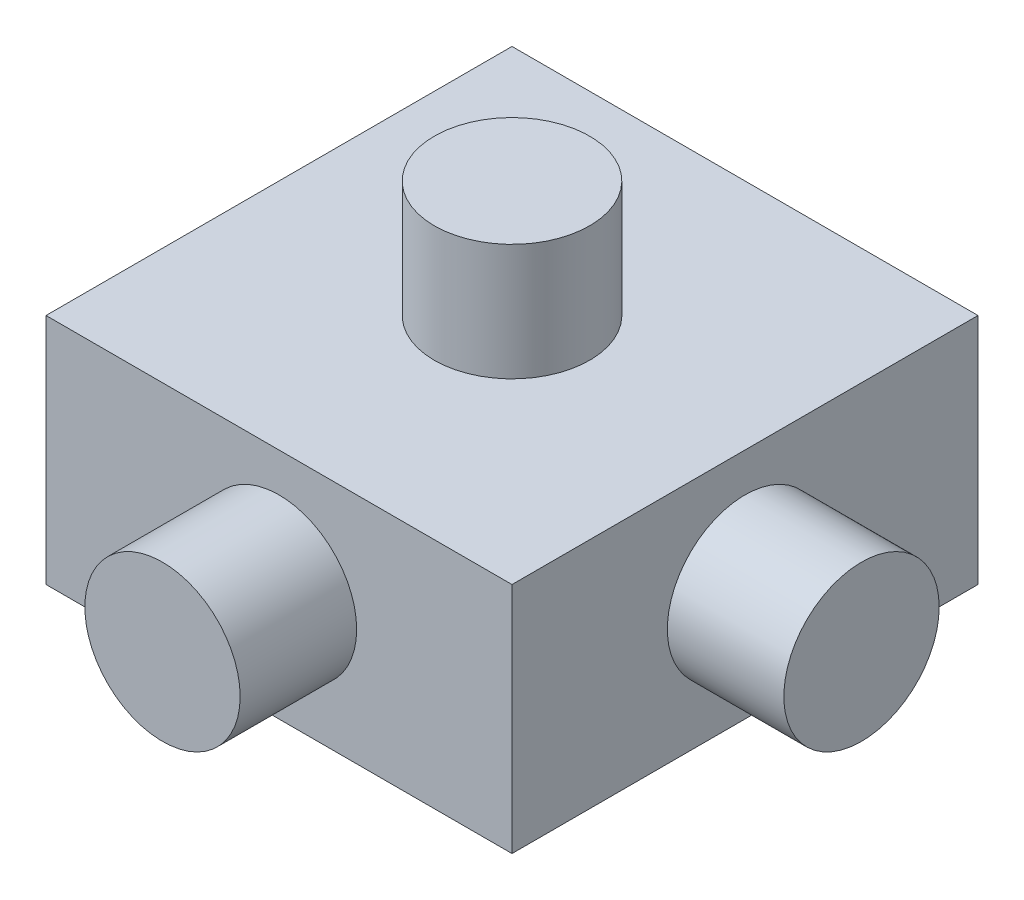
SolidWorks part; units mm, degrees
ref_plane "정면" through (0, 0, 0) normal (0, 0, 1) x (1, 0, 0)
ref_plane "윗면" through (0, 0, 0) normal (0, 1, 0) x (1, 0, 0)
ref_plane "우측면" through (0, 0, 0) normal (1, 0, 0) x (0, 0, -1)
sketch "스케치1" plane through (0, 0, 0) normal (0, 1, 0) x (1, 0, 0)
  line L1 (-42.6879, -27.3674) -> (17.3121, -27.3674)
  line L2 (-42.6879, -27.3674) -> (-42.6879, 32.6326)
  line L3 (-42.6879, 32.6326) -> (17.3121, 32.6326)
  line L4 (17.3121, -27.3674) -> (17.3121, 32.6326)
extrude "보스-돌출1" add sketch "스케치1" along normal blind 30
sketch "스케치2" plane through (17.3121, 0, 0) normal (1, 0, 0) x (0, 0, -1)
  circle A0 centre (2.6326, 15) radius 10
extrude "보스-돌출2" add sketch "스케치2" along normal blind 15 contours A0
sketch "스케치4" plane through (0, 0, 27.3674) normal (0, 0, 1) x (1, 0, 0)
  circle A0 centre (-12.6879, 15) radius 10
  point P8 (0, 0)
  point P9 (0, 0)
  point P10 (0, 0)
  point P11 (-12.6879, 15)
extrude "보스-돌출3" add sketch "스케치4" along normal blind 15
sketch "스케치5" plane through (0, 30, 0) normal (0, 1, 0) x (1, 0, 0)
  circle A0 centre (-12.6879, 2.6326) radius 10
extrude "보스-돌출4" add sketch "스케치5" along normal blind 15 contours A0
